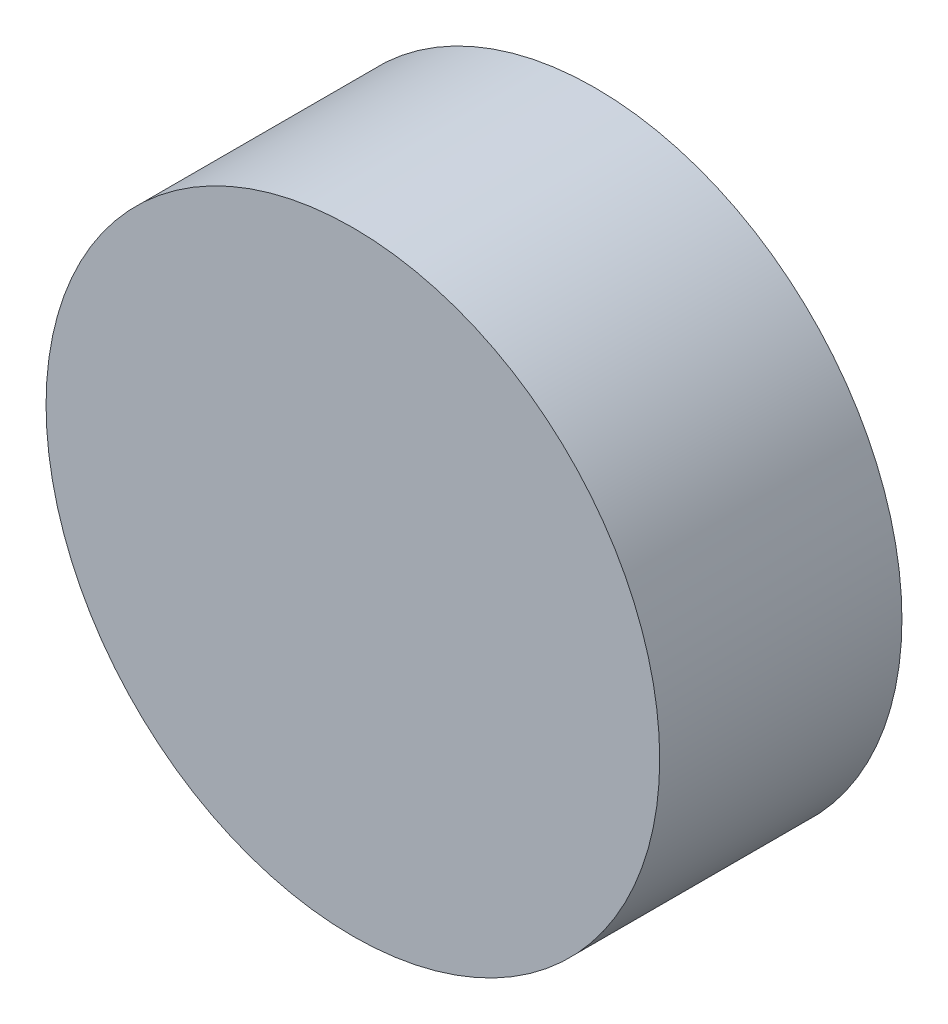
SolidWorks part; units mm, degrees
ref_plane "Plan de face" through (0, 0, 0) normal (0, 0, 1) x (1, 0, 0)
ref_plane "Plan de dessus" through (0, 0, 0) normal (0, 1, 0) x (1, 0, 0)
ref_plane "Plan de droite" through (0, 0, 0) normal (1, 0, 0) x (0, 0, -1)
sketch "Esquisse1" plane through (0, 0, 0) normal (0, 0, 1) x (1, 0, 0)
  circle A0 centre (0, 0) radius 3.8
extrude "Boss.-Extru.2" add sketch "Esquisse1" along normal blind 3 contours A0
